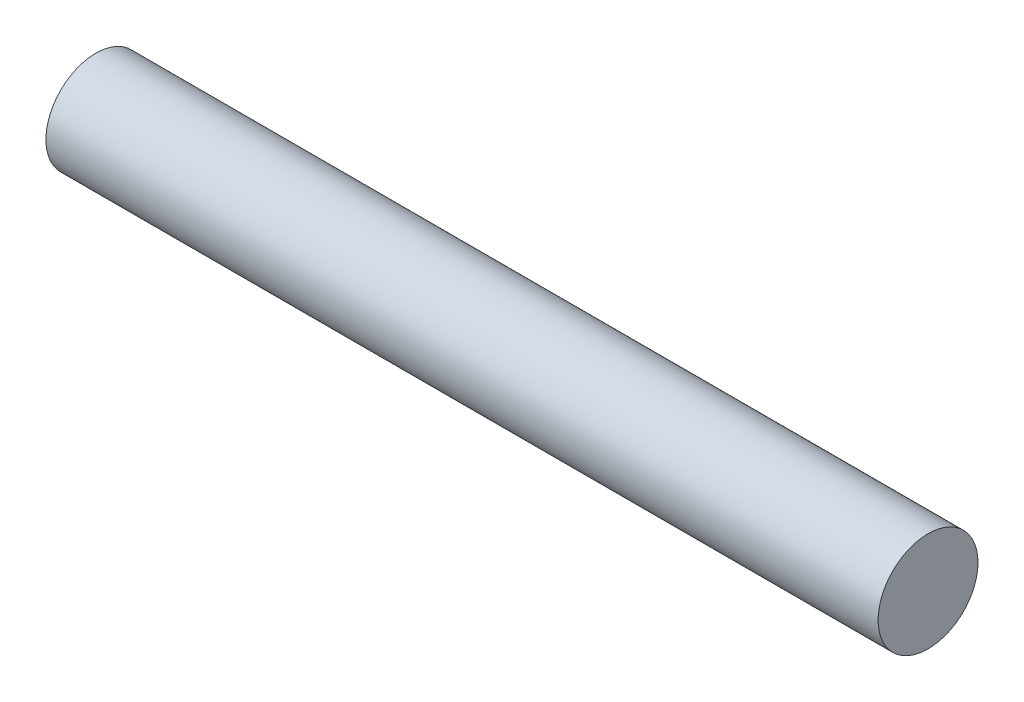
SolidWorks part; units mm, degrees
ref_plane "Front Plane" through (0, 0, 0) normal (0, 0, 1) x (1, 0, 0)
ref_plane "Top Plane" through (0, 0, 0) normal (0, 1, 0) x (1, 0, 0)
ref_plane "Right Plane" through (0, 0, 0) normal (1, 0, 0) x (0, 0, -1)
sketch "Sketch1" plane through (0, 0, 0) normal (1, 0, 0) x (0, 0, -1)
  circle A1 centre (0, 0) radius 3
  dimension "D1" = 6
extrude "Boss-Extrude1" add sketch "Sketch1" along normal mid plane 50
